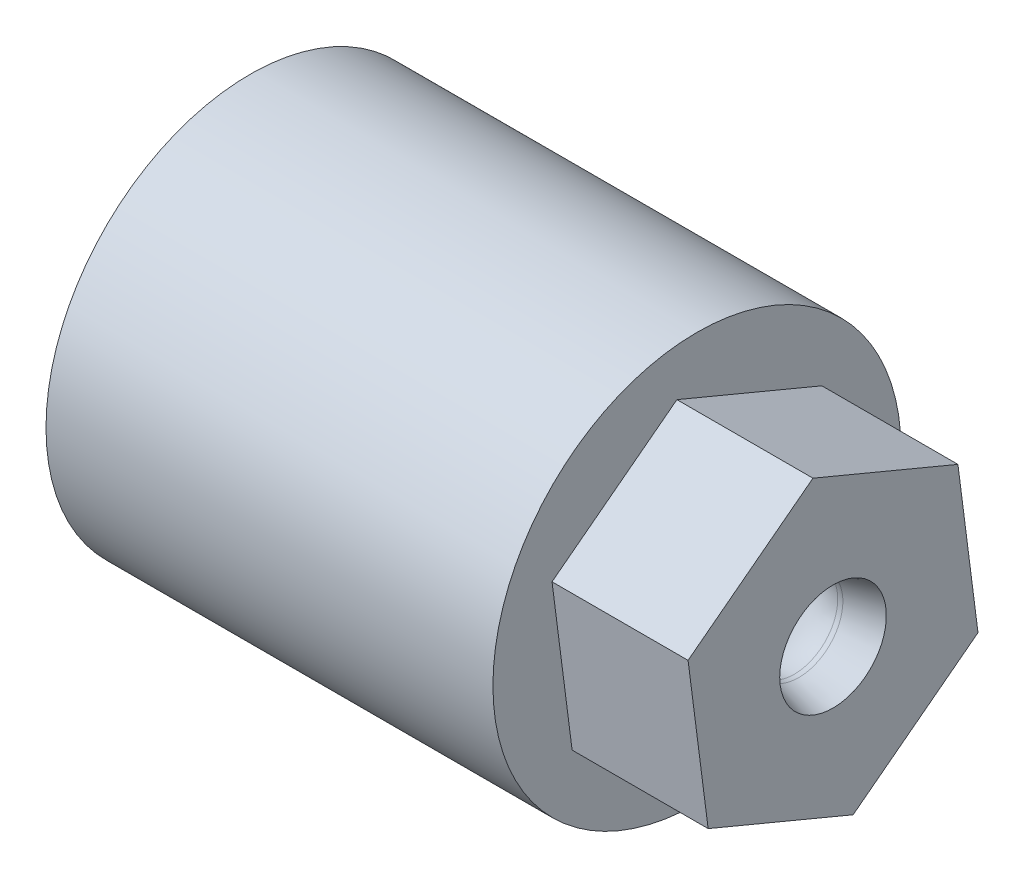
SolidWorks part; units mm, degrees
ref_plane "Front Plane" through (0, 0, 0) normal (0, 0, 1) x (1, 0, 0)
ref_plane "Top Plane" through (0, 0, 0) normal (0, 1, 0) x (1, 0, 0)
ref_plane "Right Plane" through (0, 0, 0) normal (1, 0, 0) x (0, 0, -1)
sketch "Sketch1" plane through (0, 0, 0) normal (0, 0, 1) x (1, 0, 0)
  line L0 (0, 0) -> (1.8114, 0) construction
  line L1 (0.2104, 2.0597) -> (1.8114, 2.4887)
  line L2 (-2.1553, 2.9247) -> (-4.048, 4.8174)
  line L3 (-25.4, 5.7474) -> (-25.4, 9.525)
  line L4 (-6.293, 5.7474) -> (-25.4, 5.7474)
  line L5 (-25.4, 9.525) -> (-10.8886, 9.525)
  line L6 (1.8114, 9.525) -> (1.8114, 2.4887)
  line L8 (-10.8886, 9.525) -> (1.8114, 9.525)
  arc A0 (-2.1553, 2.9247) -> (0, 2.032) centre (0, 5.08) ccw
  arc A1 (0, 2.032) -> (0.2104, 2.0597) centre (0, 2.8448) ccw
  arc A2 (-4.048, 4.8174) -> (-6.293, 5.7474) centre (-6.293, 2.5724) ccw
  dimension "D3" = 3.048
  dimension "D4" = 0.8128
  dimension "D11" = 3.175
  dimension "D1" = 2.032
  dimension "D2" = 1.8114
  dimension "D5" = 2.4887
  dimension "D6" = 15
  dimension "D7" = 45
  dimension "D8" = 5.7474
  dimension "D9" = 25.4
  dimension "D10" = 9.525
  dimension "D13" = 12.7
revolve "Revolve1" add sketch "Sketch1" angle 360 about L0
sketch "Sketch3" plane through (1.8114, 0, 0) normal (1, 0, 0) x (0, 0, -1)
  line L1 (0.9374, -7.2722) -> (6.7666, -2.8242)
  line L2 (6.7666, -2.8242) -> (5.8292, 4.4479)
  line L3 (5.8292, 4.4479) -> (-0.9374, 7.2722)
  line L4 (-0.9374, 7.2722) -> (-6.7666, 2.8242)
  line L5 (-6.7666, 2.8242) -> (-5.8292, -4.4479)
  line L6 (-5.8292, -4.4479) -> (0.9374, -7.2722)
  circle A0 centre (0, 0) radius 6.35 construction
  circle M7 centre (0, 0) radius 9.525
  dimension "D1" = 12.7
extrude "Cut-Extrude2" cut sketch "Sketch3" against normal blind 6.35 contours L6 L5 L4 L3 L2 L1 M7
equation "\"D3@Sketch1\"= 1.5 * \"D1@Sketch1\""
equation "\"D4@Sketch1\"=.4 * \"D1@Sketch1\""
equation "\"D5@Sketch1\"=\"D1@Sketch1\" * ( 1.5 ) ^ .5"
equation "\"D8@Sketch1\"=\"D1@Sketch1\" * ( 8 ) ^ .5"
equation "\"er\"= 4"
